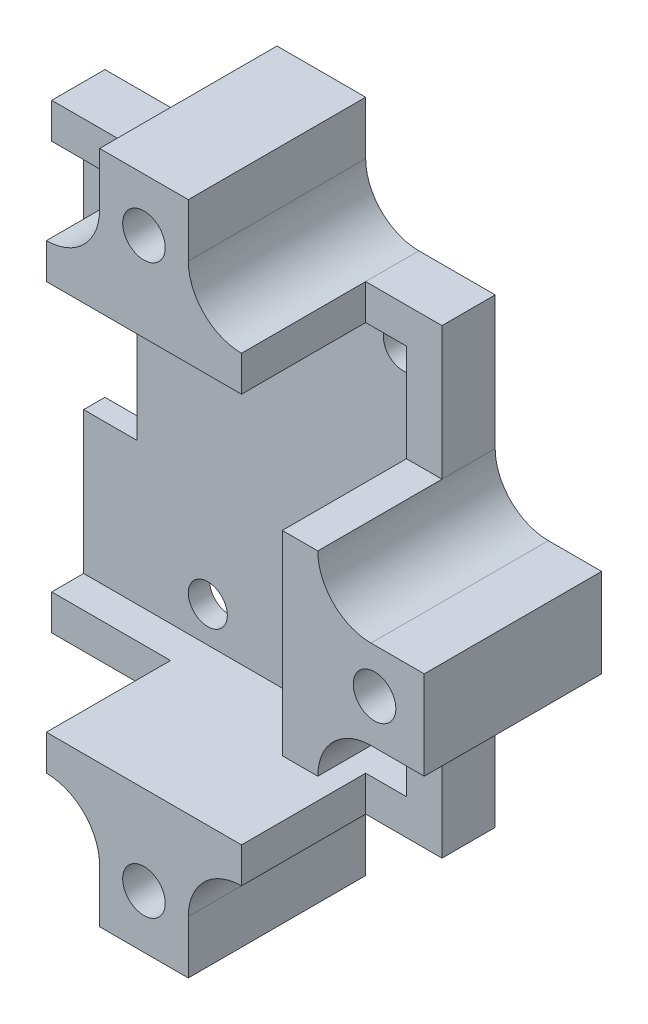
SolidWorks part; units mm, degrees
ref_plane "Front Plane" through (0, 0, 0) normal (0, 0, 1) x (1, 0, 0)
ref_plane "Top Plane" through (0, 0, 0) normal (0, 1, 0) x (1, 0, 0)
ref_plane "Right Plane" through (0, 0, 0) normal (1, 0, 0) x (0, 0, -1)
sketch "Sketch1" plane through (0, 0, 0) normal (0, 0, 1) x (1, 0, 0)
  line L0 (0, -13) -> (22, -13) construction
  line L1 (0, 0) -> (22, 0)
  line L2 (0, 0) -> (0, -10)
  line L3 (0, -26) -> (22, -26)
  line L4 (22, 0) -> (22, -26)
  line L5 (14.7, 0) -> (9.7, 0)
  line L6 (14.7, 0) -> (14.7, 6)
  line L7 (14.7, 6) -> (9.7, 6)
  line L8 (9.7, 0) -> (9.7, 6)
  line L9 (22, -10.5) -> (28, -10.5)
  line L10 (22, -10.5) -> (22, -15.5)
  line L11 (22, -15.5) -> (28, -15.5)
  line L12 (28, -10.5) -> (28, -15.5)
  line L13 (14.7, -26) -> (9.7, -26)
  line L14 (14.7, -26) -> (14.7, -32)
  line L15 (14.7, -32) -> (9.7, -32)
  line L16 (9.7, -26) -> (9.7, -32)
  line L17 (12.2, 0) -> (12.2, -26) construction
  line L18 (12.2, 3) -> (12.2, 0) construction
  line L19 (0, -16) -> (0, -26)
  line L20 (7, -4) -> (18, -4) construction
  line L21 (7, -4) -> (7, -22) construction
  line L22 (7, -22) -> (18, -22) construction
  line L23 (18, -4) -> (18, -22) construction
  line L24 (0, -10) -> (3, -10)
  line L26 (0, -16) -> (3, -16)
  line L27 (3, -10) -> (3, -16)
  circle A0 centre (12.2, -29) radius 1.2
  circle A1 centre (25.2, -13) radius 1.2
  circle A2 centre (12.2, 3) radius 1.2
  circle A3 centre (18, -4) radius 1.1
  circle A4 centre (7, -4) radius 1.1
  circle A5 centre (7, -22) radius 1.1
  circle A6 centre (18, -22) radius 1.1
  point P17 (12.2, -26)
  point P18 (22, -13)
  point P19 (22, -13)
  point P20 (12.2, 0)
  dimension "D11" = 2.4
  dimension "D12" = 2.4
  dimension "D13" = 2.4
  dimension "D22" = 2.2
  dimension "D23" = 2.2
  dimension "D24" = 2.2
  dimension "D25" = 2.2
  dimension "D1" = 6
  dimension "D2" = 6
  dimension "D3" = 26
  dimension "D4" = 22
  dimension "D5" = 5
  dimension "D6" = 9.8
  dimension "D7" = 5
  dimension "D8" = 6
  dimension "D9" = 9.8
  dimension "D10" = 5
  dimension "D14" = 16
  dimension "D15" = 13
  dimension "D16" = 16
  dimension "D17" = 9.8
  dimension "D18" = 18
  dimension "D19" = 11
  dimension "D20" = 4
  dimension "D21" = 4
  dimension "D26" = 3
  dimension "D27" = 6
  dimension "D28" = 3
extrude "Boss-Extrude1" add sketch "Sketch1" along normal blind 10 contours L4 L1 L2 L3 | L8 L1 L6 L7 | L12 L9 L4 L11 | L3 L16 L15 L14
fillet "Fillet1" radius 3 6 edges at (9.7, 0, 5) (14.7, 0, 5) (22, -10.5, 5) (22, -15.5, 5) (14.7, -26, 5) (9.7, -26, 5)
sketch "Sketch2" plane through (0, 0, 10) normal (0, 0, 1) x (1, 0, 0)
  line L0 (14.7, 6) -> (9.7, 6) construction
  line L1 (-8, -2) -> (20, -2)
  line L2 (-8, -2) -> (-8, -24)
  line L3 (-8, -24) -> (20, -24)
  line L4 (20, -2) -> (20, -24)
  line L5 (20, -13) -> (28, -13) construction
  line L6 (28, -10.5) -> (28, -15.5) construction
  point P6 (12.2, 6)
  dimension "D1" = 28
  dimension "D2" = 22
  dimension "D3" = 7.8
extrude "Cut-Extrude1" cut sketch "Sketch2" against normal blind 8.8
sketch "Sketch3" plane through (0, 0, 10) normal (0, 0, 1) x (1, 0, 0)
  line L1 (0, 0) -> (6.7, 0)
  line L2 (0, 0) -> (0, -26)
  line L3 (0, -26) -> (6.7, -26)
  line L4 (6.7, 0) -> (6.7, -26)
  line L5 (17.7, 0) -> (22, 0)
  line L6 (17.7, 0) -> (17.7, -7.5)
  line L7 (17.7, -7.5) -> (22, -7.5)
  line L8 (22, 0) -> (22, -7.5)
  line L9 (22, -18.5) -> (17.7, -18.5)
  line L10 (22, -18.5) -> (22, -26)
  line L11 (22, -26) -> (17.7, -26)
  line L12 (17.7, -18.5) -> (17.7, -26)
extrude "Cut-Extrude2" cut sketch "Sketch3" against normal blind 7
